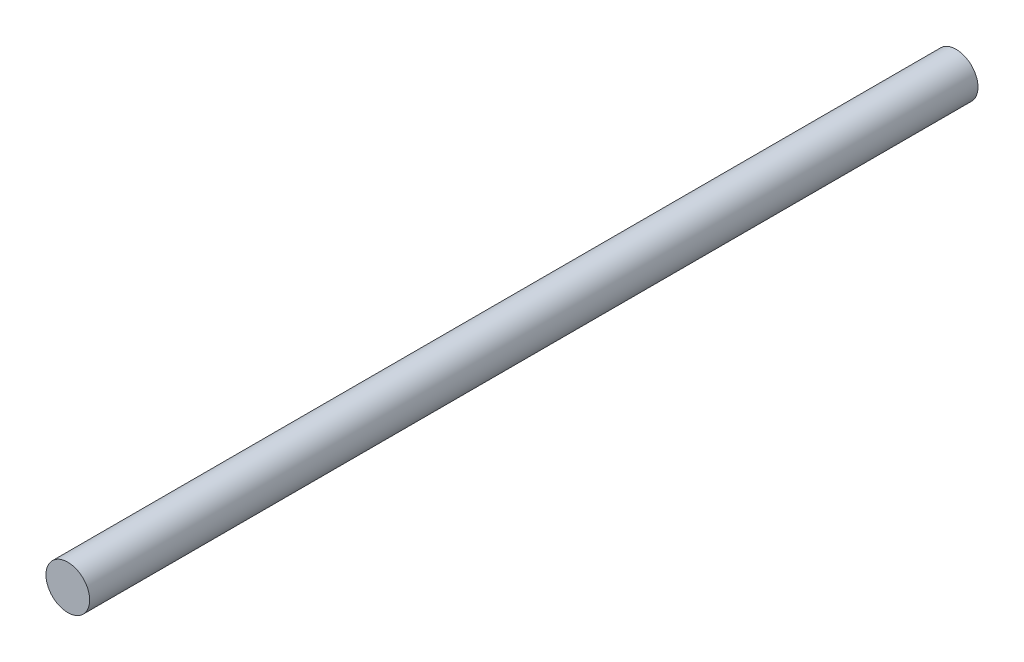
SolidWorks part; units mm, degrees
ref_plane "前视基准面" through (0, 0, 0) normal (0, 0, 1) x (1, 0, 0)
ref_plane "上视基准面" through (0, 0, 0) normal (0, 1, 0) x (1, 0, 0)
ref_plane "右视基准面" through (0, 0, 0) normal (1, 0, 0) x (0, 0, -1)
sketch "草图1" plane through (0, 0, 0) normal (0, 0, 1) x (1, 0, 0)
  circle A0 centre (0, 0) radius 1.65
  dimension "D1" = 3.3
extrude "凸台-拉伸1" add sketch "草图1" along normal blind 67.05
